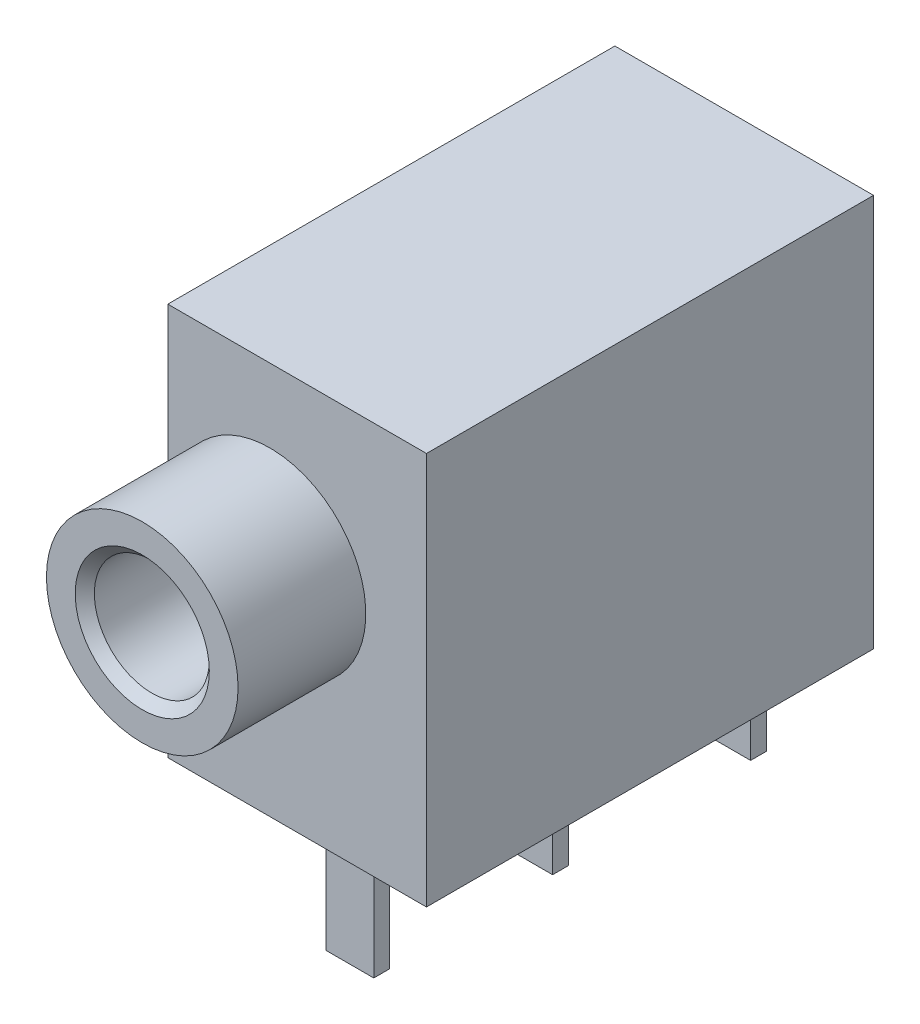
SolidWorks part; units mm, degrees
ref_plane "Front Plane" through (0, 0, 0) normal (0, 0, 1) x (1, 0, 0)
ref_plane "Top Plane" through (0, 0, 0) normal (0, 1, 0) x (1, 0, 0)
ref_plane "Right Plane" through (0, 0, 0) normal (1, 0, 0) x (0, 0, -1)
sketch "Sketch1" plane through (0, 0, 0) normal (0, 0, 1) x (1, 0, 0)
  line L1 (-4.05, -6.15) -> (4.05, -6.15)
  line L2 (-4.05, -6.15) -> (-4.05, 6.15)
  line L3 (-4.05, 6.15) -> (4.05, 6.15)
  line L4 (4.05, -6.15) -> (4.05, 6.15)
  line L5 (-4.05, -6.15) -> (4.05, 6.15) construction
  line L6 (-4.05, 6.15) -> (4.05, -6.15) construction
  point P0 (0, 0)
  dimension "D1" = 8.1
  dimension "D2" = 12.3
extrude "Boss-Extrude1" add sketch "Sketch1" along normal mid plane 14
sketch "Sketch2" plane through (0, 0, 7) normal (0, 0, 1) x (1, 0, 0)
  line L0 (4.05, 6.15) -> (-4.05, 6.15) construction
  line L1 (-4.05, 6.15) -> (-4.05, -6.15) construction
  circle A0 centre (-0.85, 0.85) radius 3
  dimension "D1" = 5.3
  dimension "D3" = 6
  dimension "D2" = 3.2
extrude "Boss-Extrude2" add sketch "Sketch2" along normal blind 4
sketch "Sketch3" plane through (0, 0, 11) normal (0, 0, 1) x (1, 0, 0)
  circle A1 centre (-0.85, 0.85) radius 1.8
  circle A2 centre (-0.85, 0.85) radius 3 construction
  dimension "D1" = 3.6
extrude "Cut-Extrude1" cut sketch "Sketch3" against normal blind 14
chamfer "Chamfer1" distance 0.3 angle 45 1 edges at (0.95, 0.85, 11)
sketch "Sketch4" plane through (0, -6.15, 0) normal (0, -1, 0) x (1, 0, 0)
  line L0 (-4.05, -7) -> (4.05, -7) construction
  line L1 (0.15, 6.25) -> (1.65, 6.25)
  line L2 (0.15, 6.25) -> (0.15, 5.75)
  line L3 (0.15, 5.75) -> (1.65, 5.75)
  line L4 (1.65, 6.25) -> (1.65, 5.75)
  line L5 (-1.85, 2.55) -> (-0.35, 2.55)
  line L6 (-1.85, 2.55) -> (-1.85, 2.05)
  line L7 (-1.85, 2.05) -> (-0.35, 2.05)
  line L8 (-0.35, 2.55) -> (-0.35, 2.05)
  line L9 (0.15, 0.65) -> (1.65, 0.65)
  line L10 (0.15, 0.65) -> (0.15, 0.15)
  line L11 (0.15, 0.15) -> (1.65, 0.15)
  line L12 (1.65, 0.65) -> (1.65, 0.15)
  line L13 (-1.85, -3.05) -> (-0.35, -3.05)
  line L14 (-1.85, -3.05) -> (-1.85, -3.55)
  line L15 (-1.85, -3.55) -> (-0.35, -3.55)
  line L16 (-0.35, -3.05) -> (-0.35, -3.55)
  line L17 (0.15, -5.55) -> (1.65, -5.55)
  line L18 (0.15, -5.55) -> (0.15, -6.05)
  line L19 (0.15, -6.05) -> (1.65, -6.05)
  line L20 (1.65, -5.55) -> (1.65, -6.05)
  point P20 (-1.1, 2.55)
  point P21 (-1.1, -3.05)
  point P22 (0.9, -5.55)
  point P23 (0.9, 0.65)
  point P26 (0.9, 6.25)
  point P29 (1.65, 6)
  point P32 (-1.85, 2.3)
  point P33 (1.65, 0.4)
  point P34 (-1.85, -3.3)
  point P35 (1.65, -5.8)
  dimension "D1" = 2
  dimension "D2" = 1.5
  dimension "D3" = 0.5
  dimension "D4" = 0.9
  dimension "D5" = 13
  dimension "D6" = 9.3
  dimension "D7" = 7.4
  dimension "D8" = 3.7
  dimension "D9" = 1.2
extrude "Boss-Extrude3" add sketch "Sketch4" along normal blind 3.5
